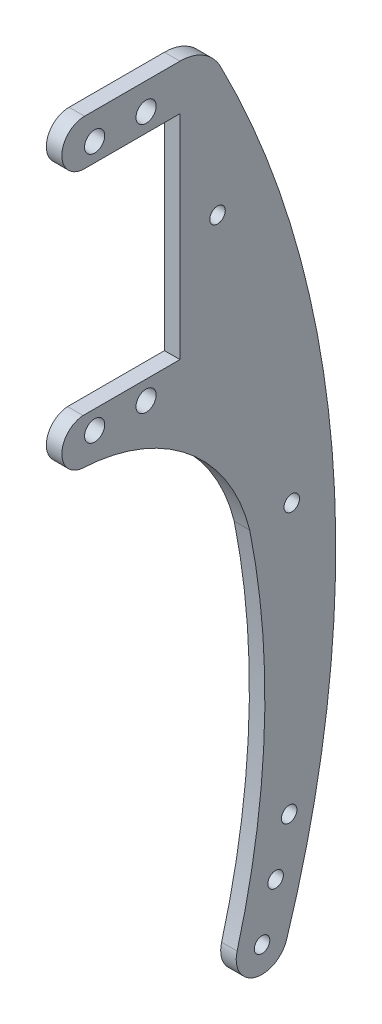
SolidWorks part; units mm, degrees
ref_plane "Front Plane" through (0, 0, 0) normal (0, 0, 1) x (1, 0, 0)
ref_plane "Top Plane" through (0, 0, 0) normal (0, 1, 0) x (1, 0, 0)
ref_plane "Right Plane" through (0, 0, 0) normal (1, 0, 0) x (0, 0, -1)
sketch "Sketch1" plane through (0, 0, 0) normal (1, 0, 0) x (0, 0, -1)
  line L0 (0, 30.2358) -> (0, -30.2358) construction
  line L1 (-38.866, 0) -> (38.866, 0) construction
  line L2 (-6.925, 25.0125) -> (11.525, 25.0125) construction
  line L3 (-6.925, 29.4125) -> (11.525, 29.4125)
  line L4 (-6.925, 20.6125) -> (11.525, 20.6125)
  line L5 (-6.925, 29.4125) -> (-6.925, 20.6125) construction
  line L6 (11.525, 22.2625) -> (-6.925, 22.2625) construction
  line L7 (11.525, -22.2625) -> (-6.925, -22.2625) construction
  line L8 (-6.925, -24.9839) -> (11.525, -24.9839) construction
  line L10 (-7.2193, -20.5938) -> (11.525, -20.5938)
  line L11 (11.525, 20.6125) -> (11.525, -20.5938)
  line L12 (-4.975, 24.2125) -> (-4.975, -24.2125) construction
  line L13 (3.025, 24.2125) -> (3.025, -24.2125) construction
  line L14 (-11.325, 25.0125) -> (-11.325, -24.9839) construction
  line L15 (17.295, 0) -> (17.295, 5.0237) construction
  line L16 (18.795, 0) -> (33.1599, -55.4185) construction
  line L17 (32.6637, -107.3162) -> (27.4085, -126.5616) construction
  line L18 (33.1599, -55.4185) -> (32.6637, -107.3162) construction
  line L19 (4.975, -24.2125) -> (33.1599, -55.4185) construction
  line L20 (4.975, -24.2125) -> (32.6637, -107.3162) construction
  line L21 (-4.975, -24.2125) -> (27.4085, -126.5616) construction
  line L22 (33.1599, -55.4185) -> (25.0249, -55.9181) construction
  line L23 (31.4143, -51.4662) -> (31.947, -60.1411) construction
  line L24 (27.4085, -126.5616) -> (32.171, -128.0842) construction
  line L25 (33.1599, -55.4185) -> (41.2949, -54.919) construction
  line L26 (27.4085, -126.5616) -> (22.5876, -125.2353) construction
  line L27 (11.525, 29.4125) -> (11.525, 20.6125) construction
  circle A0 centre (-4.975, 24.2125) radius 1.95
  circle A1 centre (4.975, 24.2125) radius 1.95
  circle A2 centre (4.975, -24.2125) radius 1.95
  circle A3 centre (-4.975, -24.2125) radius 1.95
  arc A4 (-6.925, 29.4125) -> (-6.925, 20.6125) centre (-6.925, 25.0125) ccw
  arc A6 (-7.2193, -29.3741) -> (-7.2193, -20.5938) centre (-6.925, -24.9839) cw
  circle A8 centre (18.795, 0) radius 1.5
  circle A9 centre (33.1599, -55.4185) radius 1.5
  circle A10 centre (32.6637, -107.3162) radius 1.5
  circle A11 centre (30.0361, -116.9389) radius 1.5
  circle A12 centre (27.4085, -126.5616) radius 1.5
  arc A14 (11.525, 29.4125) -> (19.3426, 24.653) centre (11.525, 20.6125) cw
  arc A15 (32.171, -128.0842) -> (19.3426, 24.653) centre (-158.3291, -67.1771) ccw
  arc A16 (22.5876, -125.2353) -> (25.0249, -55.9181) centre (-122.0396, -85.4487) ccw
  arc A17 (25.0249, -55.9181) -> (-7.2193, -29.3741) centre (-8.9489, -64.3313) ccw
  arc A18 (22.5876, -125.2353) -> (32.171, -128.0842) centre (27.4085, -126.5616) ccw
  point P3 (0, 0)
  point P6 (0, 0)
  point P17 (3.5761, 25.0125)
  point P30 (2.3, -24.9933)
  dimension "D1" = 3.9
  dimension "D4" = 4.4
  dimension "D7" = 3
  dimension "D14" = 5
  dimension "D18" = 150
  dimension "D19" = 35
  dimension "D20" = 200
  dimension "D2" = 9.95
  dimension "D3" = 48.425
  dimension "D5" = 3.6
  dimension "D6" = 16.5
  dimension "D8" = 5.77
  dimension "D9" = 19.95
  dimension "D10" = 51.9
  dimension "D11" = 42.05
  dimension "D12" = 87.595
  dimension "D13" = 107.35
  dimension "D15" = 8.8
  dimension "D16" = 57.25
  dimension "D21" = 41.2063
  dimension "D22" = 4.3901
extrude "Boss-Extrude1" add sketch "Sketch1" along normal blind 3
